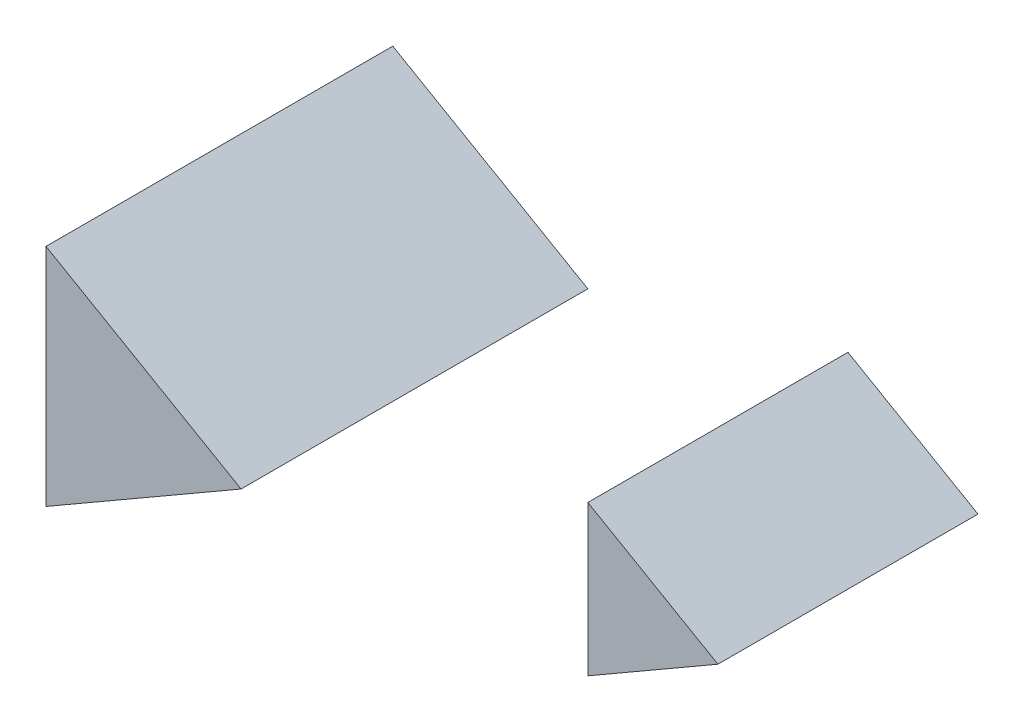
SolidWorks part; units mm, degrees
ref_plane "前视基准面" through (0, 0, 0) normal (0, 0, 1) x (1, 0, 0)
ref_plane "上视基准面" through (0, 0, 0) normal (0, 1, 0) x (1, 0, 0)
ref_plane "右视基准面" through (0, 0, 0) normal (1, 0, 0) x (0, 0, -1)
other "Configuration Table"
sketch "草图1" plane through (0, 0, 0) normal (0, 0, 1) x (1, 0, 0)
  line L1 (-200, 0) -> (-650, 259.8076)
  line L2 (-650, 259.8076) -> (-650, -259.8076)
  line L3 (-650, -259.8076) -> (-200, 0)
  circle A0 centre (-500, 0) radius 150 construction
extrude "凸台-拉伸1" add sketch "草图1" along normal blind 800
sketch "草图2" plane through (0, 0, 0) normal (0, 0, 1) x (1, 0, 0)
  line L1 (700, 0) -> (400, 173.2051)
  line L2 (400, 173.2051) -> (400, -173.2051)
  line L3 (400, -173.2051) -> (700, 0)
  circle A0 centre (500, 0) radius 100 construction
extrude "凸台-拉伸2" add sketch "草图2" along normal blind 600
